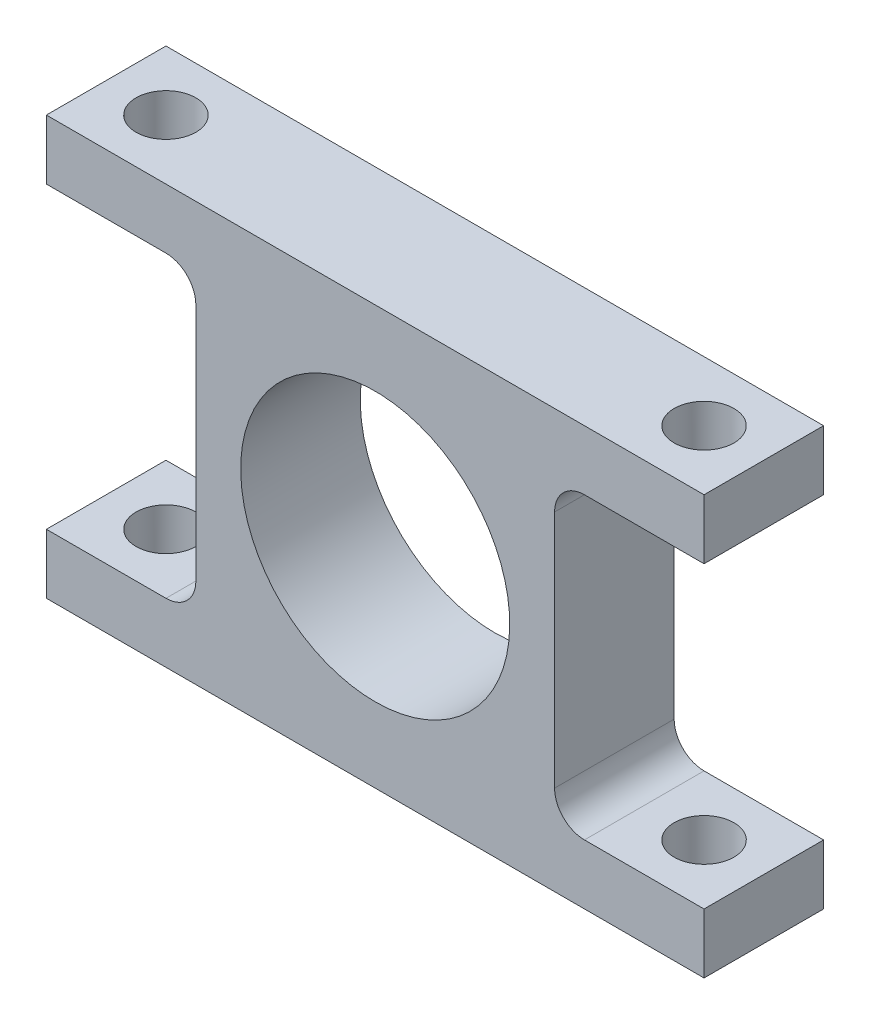
SolidWorks part; units mm, degrees
material "POM 乙缩醛共聚物"
ref_plane "前视基准面" through (0, 0, 0) normal (0, 0, 1) x (1, 0, 0)
ref_plane "上视基准面" through (0, 0, 0) normal (0, 1, 0) x (1, 0, 0)
ref_plane "右视基准面" through (0, 0, 0) normal (1, 0, 0) x (0, 0, -1)
sketch "草图1" plane through (0, 0, 0) normal (0, 0, 1) x (1, 0, 0)
  line L0 (0, 0) -> (0, 24.3091) construction
  line L1 (22, 0) -> (-22, 0)
  line L2 (-22, 0) -> (-22, 4)
  line L3 (22, 0) -> (22, 4)
  line L4 (-22, 4) -> (-12, 4)
  line L5 (22, 4) -> (12, 4)
  line L6 (-12, 4) -> (-12, 24)
  line L7 (12, 4) -> (12, 24)
  line L8 (-12, 24) -> (-22, 24)
  line L9 (12, 24) -> (22, 24)
  line L10 (-22, 24) -> (-22, 28)
  line L11 (22, 24) -> (22, 28)
  line L12 (-22, 28) -> (22, 28)
  point P16 (0, 28)
  dimension "D1" = 28
  dimension "D2" = 44
  dimension "D3" = 24
  dimension "D4" = 4
  dimension "D5" = 4
extrude "凸台-拉伸1" add sketch "草图1" along normal blind 8
sketch "草图2" plane through (0, 0, 8) normal (0, 0, 1) x (1, 0, 0)
  line L0 (0, 28) -> (0, 0) construction
  line L1 (22, 28) -> (-22, 28) construction
  line L2 (0, 14) -> (9, 14) construction
  ellipse E0 centre (0, 14) end of major axis (-9, 14) minor radius 9
  dimension "D1" = 9
  dimension "D2" = 9
extrude "切除-拉伸1" cut sketch "草图2" against normal through all
fillet "圆角1" radius 2 4 edges at (12, 24, 4) (12, 4, 4) (-12, 4, 4) (-12, 24, 4)
sketch "草图3" plane through (0, 28, 0) normal (0, 1, 0) x (1, 0, 0)
  line L0 (-22, -4) -> (22, -4) construction
  line L1 (-22, -8) -> (-22, 0) construction
  line L2 (22, -8) -> (22, 0) construction
  line L3 (0, 0) -> (0, -4) construction
  line L4 (22, 0) -> (-22, 0) construction
  circle A0 centre (-18, -4) radius 2
  circle A1 centre (18, -4) radius 2
  dimension "D1" = 4
  dimension "D2" = 4
extrude "切除-拉伸2" cut sketch "草图3" against normal through all
